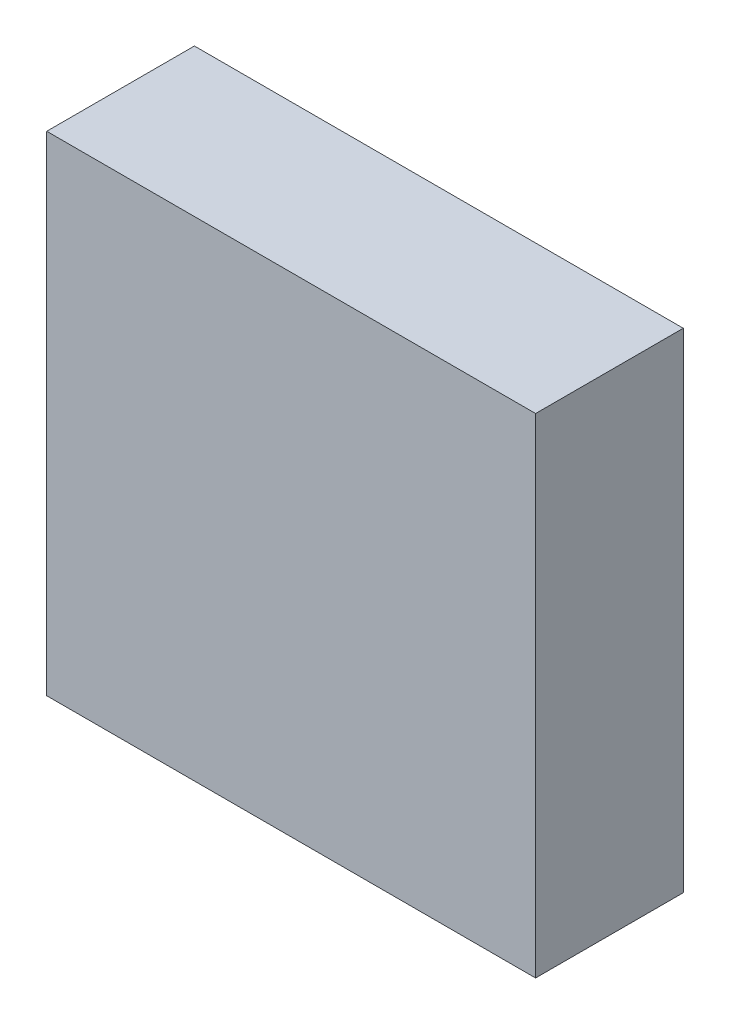
SolidWorks part; units mm, degrees
ref_plane "前视基准面" through (0, 0, 0) normal (0, 0, 1) x (1, 0, 0)
ref_plane "上视基准面" through (0, 0, 0) normal (0, 1, 0) x (1, 0, 0)
ref_plane "右视基准面" through (0, 0, 0) normal (1, 0, 0) x (0, 0, -1)
other "Configuration Table"
sketch "草图1" plane through (0, 0, 0) normal (0, 0, 1) x (1, 0, 0)
  line L0 (0, 0) -> (36, 0)
  line L1 (36, 0) -> (36, 36)
  line L2 (36, 36) -> (0, 36)
  line L3 (0, 36) -> (0, 0)
  dimension "width" = 36
  dimension "height" = 36
extrude "Screw_foot_pad" add sketch "草图1" along normal blind 10.8752
